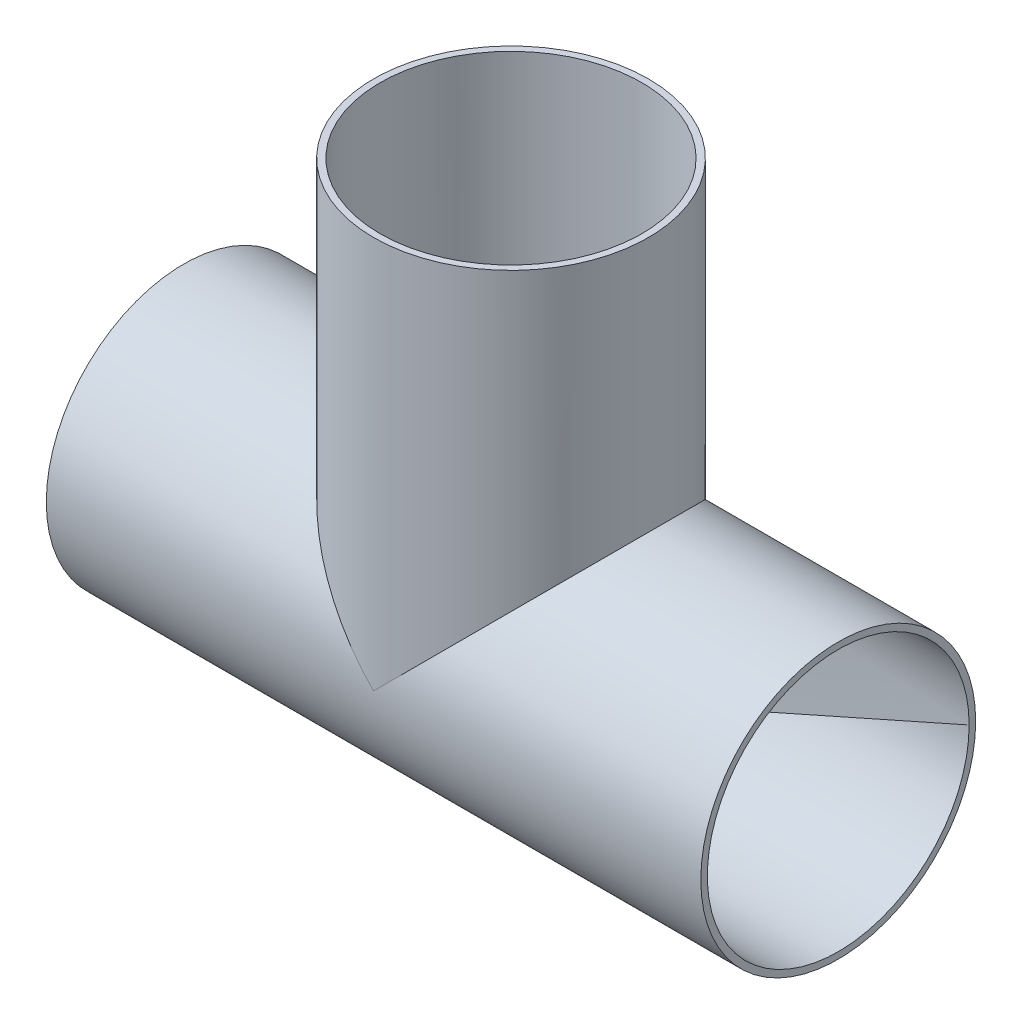
SolidWorks part; units mm, degrees
ref_plane "Front Plane" through (0, 0, 0) normal (0, 0, 1) x (1, 0, 0)
ref_plane "Top Plane" through (0, 0, 0) normal (0, 1, 0) x (1, 0, 0)
ref_plane "Right Plane" through (0, 0, 0) normal (1, 0, 0) x (0, 0, -1)
sketch "Sketch1" plane through (0, 0, 0) normal (1, 0, 0) x (0, 0, -1)
  circle A0 centre (0, 0) radius 50
  circle A1 centre (0, 0) radius 52.5
  dimension "D1" = 100
  dimension "D2" = 105
extrude "Boss-Extrude1" add sketch "Sketch1" along normal mid plane 250
sketch "Sketch2" plane through (0, 0, 0) normal (0, 1, 0) x (1, 0, 0)
  circle A0 centre (0, 0) radius 50
  circle A1 centre (0, 0) radius 52.5
  dimension "D1" = 100
  dimension "D2" = 105
extrude "Boss-Extrude2" add sketch "Sketch2" along normal blind 150
sketch "Sketch3" plane through (0, 150, 0) normal (0, 1, 0) x (1, 0, 0)
  circle A0 centre (0, 0) radius 50
extrude "Cut-Extrude1" cut sketch "Sketch3" against normal up to next
sketch "Sketch6" plane through (-125, 0, 0) normal (-1, 0, 0) x (0, 0, 1)
  circle A0 centre (0, 0) radius 50
extrude "Cut-Extrude2" cut sketch "Sketch6" against normal through all
